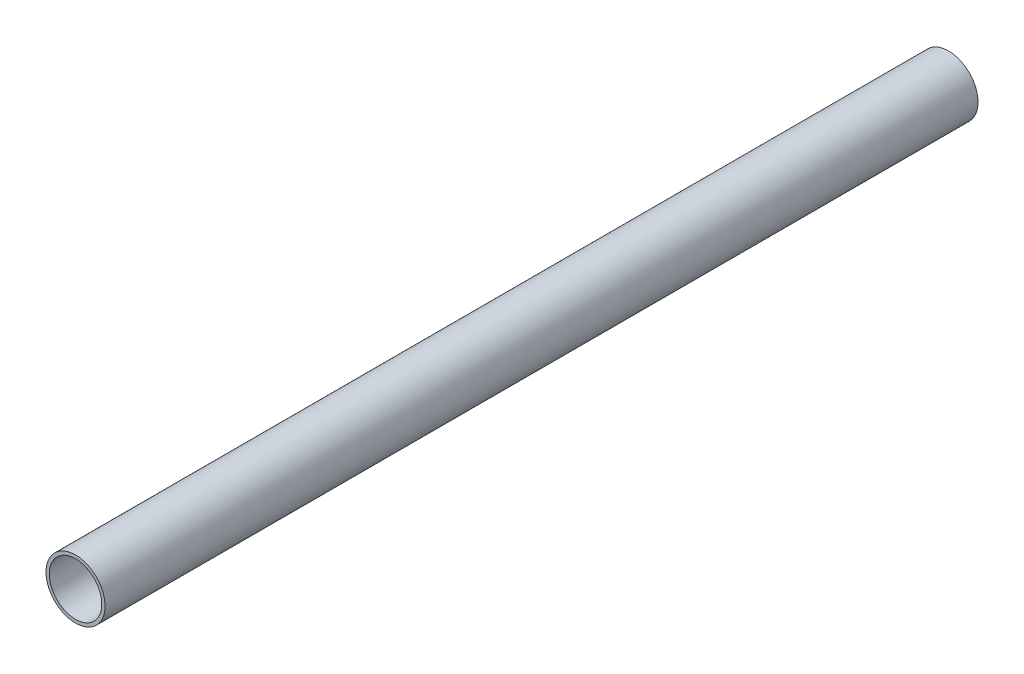
SolidWorks part; units mm, degrees
material "Thornel Mat VMA"
ref_plane "Front Plane" through (0, 0, 0) normal (0, 0, 1) x (1, 0, 0)
ref_plane "Top Plane" through (0, 0, 0) normal (0, 1, 0) x (1, 0, 0)
ref_plane "Right Plane" through (0, 0, 0) normal (1, 0, 0) x (0, 0, -1)
sketch "Sketch1" plane through (0, 0, 0) normal (0, 0, 1) x (1, 0, 0)
  circle A0 centre (0, 0) radius 9
  dimension "D1" = 18
extrude "Boss-Extrude1" add sketch "Sketch1" along normal blind 265.98
shell "Shell1" thickness 1
equation "\"fuse_diam\"= 0.07"
equation "\"fuse_rad\"= 0.035"
equation "\"battery_length\"= 0.076"
equation "\"battery_width\"= 0.034"
equation "\"battery_height\"= 0.051"
equation "\"bat_bay_length\"= 0.096"
equation "\"wing_shelf\"= 0.0175"
equation "\"shell\"= 0.002"
equation "\"chord_length\"= 0.09"
equation "\"tail_length\"= 0.26598000000000005"
equation "\"tail_diam\"= 0.035"
equation "\"connector\"= 0.06649500000000001"
equation "\"D1@Boss-Extrude1\"=\"tail_length\""
